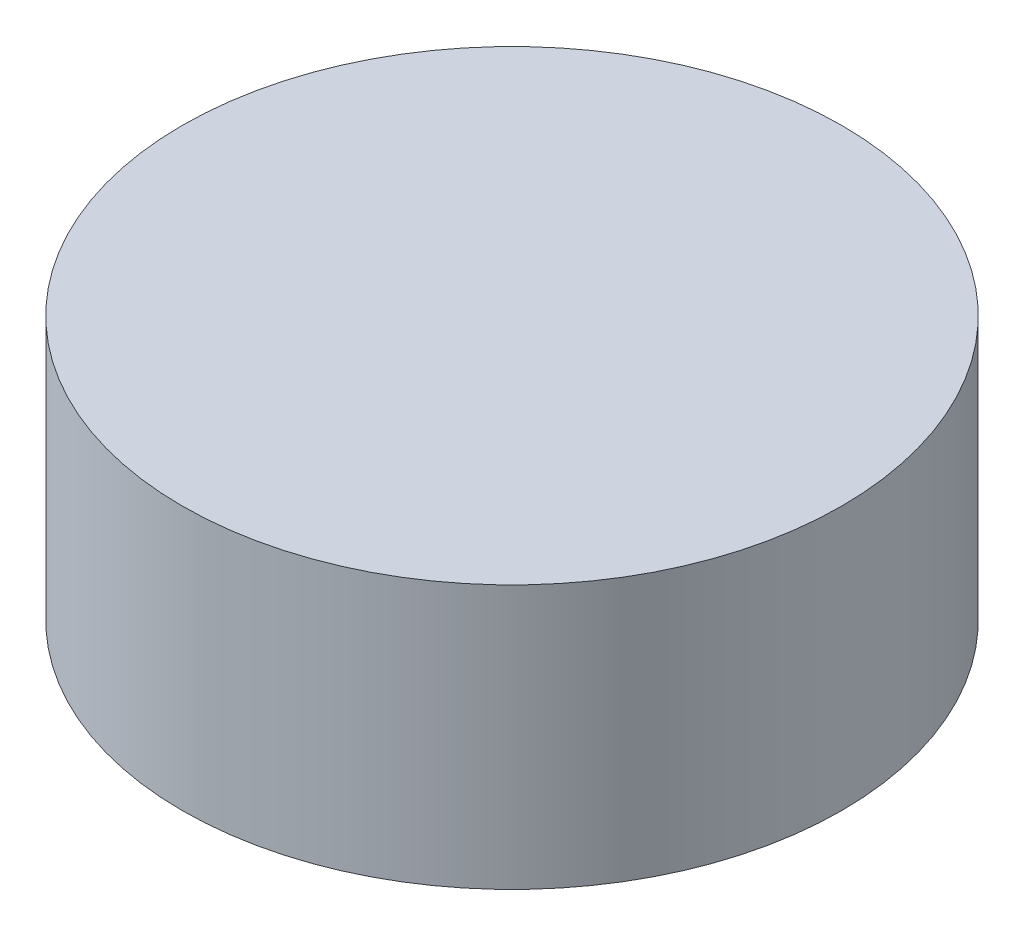
SolidWorks part; units mm, degrees
ref_plane "Front Plane" through (0, 0, 0) normal (0, 0, 1) x (1, 0, 0)
ref_plane "Top Plane" through (0, 0, 0) normal (0, 1, 0) x (1, 0, 0)
ref_plane "Right Plane" through (0, 0, 0) normal (1, 0, 0) x (0, 0, -1)
sketch "Sketch1" plane through (0, 0, 0) normal (0, 1, 0) x (1, 0, 0)
  circle A0 centre (0, 0) radius 3.175
  dimension "D1" = 6.35
extrude "Boss-Extrude1" add sketch "Sketch1" along normal blind 2.54
